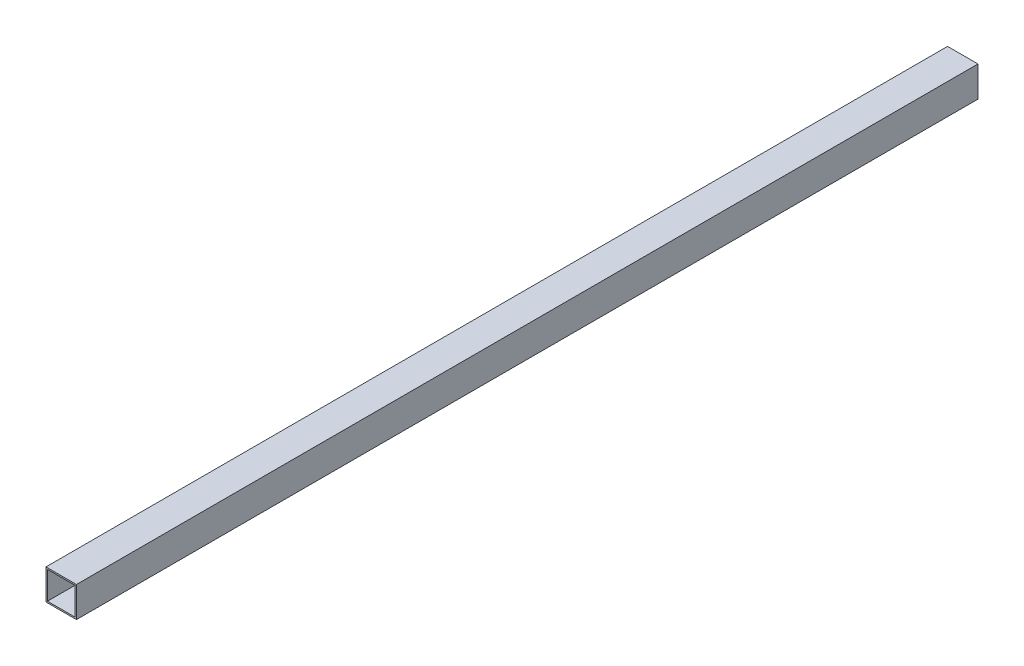
SolidWorks part; units mm, degrees
ref_plane "Front Plane" through (0, 0, 0) normal (0, 0, 1) x (1, 0, 0)
ref_plane "Top Plane" through (0, 0, 0) normal (0, 1, 0) x (1, 0, 0)
ref_plane "Right Plane" through (0, 0, 0) normal (1, 0, 0) x (0, 0, -1)
sketch "Sketch1" plane through (0, 0, 0) normal (0, 0, 1) x (1, 0, 0)
  line L0 (0, 0) -> (780, 0) construction
  line L1 (-12.5, -12.5) -> (12.5, -12.5)
  line L2 (-12.5, -12.5) -> (-12.5, 12.5)
  line L3 (-12.5, 12.5) -> (12.5, 12.5)
  line L4 (12.5, -12.5) -> (12.5, 12.5)
  line L5 (-12.5, -12.5) -> (12.5, 12.5) construction
  line L6 (-12.5, 12.5) -> (12.5, -12.5) construction
  line L7 (-11.3, 11.3) -> (11.3, 11.3)
  line L8 (11.3, -11.3) -> (11.3, 11.3)
  line L9 (-11.3, -11.3) -> (11.3, -11.3)
  line L10 (-11.3, -11.3) -> (-11.3, 11.3)
  point P0 (0, 0)
  dimension "D1" = 25
  dimension "D2" = 25
  dimension "D3" = 1.2
extrude "Boss-Extrude1" add sketch "Sketch1" along normal blind 740
